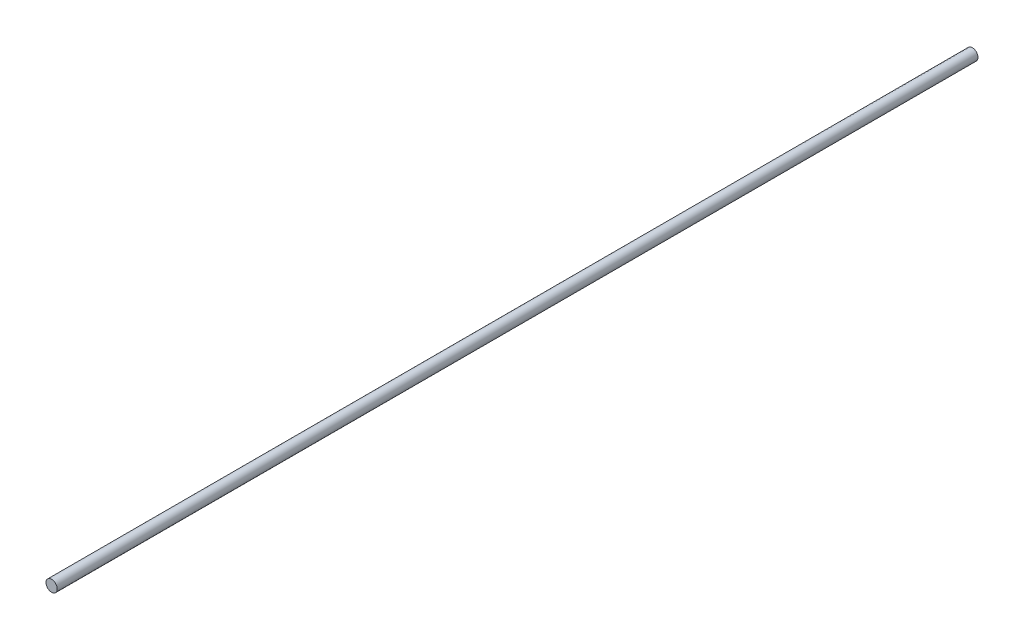
SolidWorks part; units mm, degrees
ref_plane "정면" through (0, 0, 0) normal (0, 0, 1) x (1, 0, 0)
ref_plane "윗면" through (0, 0, 0) normal (0, 1, 0) x (1, 0, 0)
ref_plane "우측면" through (0, 0, 0) normal (1, 0, 0) x (0, 0, -1)
sketch "스케치1" plane through (0, 0, 0) normal (0, 0, 1) x (1, 0, 0)
  circle A0 centre (0, 0) radius 4
extrude "보스-돌출1" add sketch "스케치1" along normal blind 640 contours A0
sketch "스케치2" plane through (0, 0, 640) normal (0, 0, 1) x (1, 0, 0)
  circle A0 centre (0, 0) radius 4
extrude "보스-돌출2" add sketch "스케치2" along normal blind 13.91
